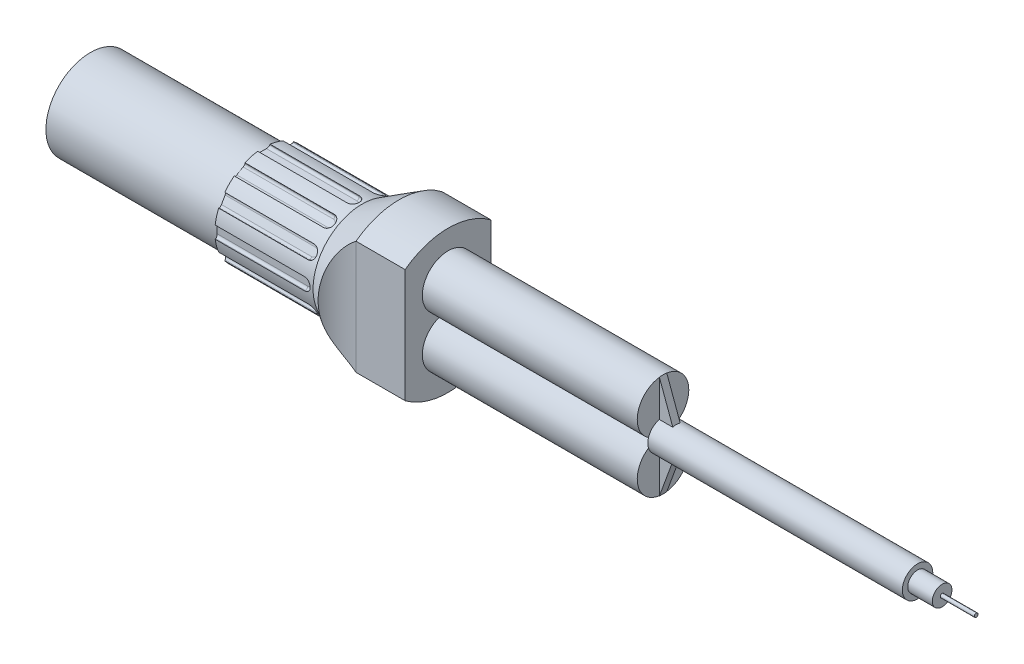
SolidWorks part; units mm, degrees
ref_plane "Ebene vorne" through (0, 0, 0) normal (0, 0, 1) x (1, 0, 0)
ref_plane "Ebene oben" through (0, 0, 0) normal (0, 1, 0) x (1, 0, 0)
ref_plane "Ebene rechts" through (0, 0, 0) normal (1, 0, 0) x (0, 0, -1)
sketch "Skizze1" plane through (0, 0, 0) normal (0, 1, 0) x (1, 0, 0)
  line L0 (0, 0) -> (0, 3.75)
  line L1 (0, 3.75) -> (3, 3.75)
  line L2 (3, 3.75) -> (8, 18.1)
  line L3 (8, 18.1) -> (78, 18.1)
  line L4 (78, 18.1) -> (78.662, 20)
  line L5 (78.662, 20) -> (118.662, 20)
  line L6 (118.662, 20) -> (133.662, 29)
  line L7 (133.662, 29) -> (153.662, 29)
  line L8 (153.662, 29) -> (153.662, 0)
  line L9 (153.662, 0) -> (0, 0) construction
  line L10 (0, 0) -> (153.662, 0)
  dimension "D1" = 7.5
  dimension "D2" = 3
  dimension "D3" = 36.2
  dimension "D4" = 5
  dimension "D5" = 70
  dimension "D6" = 58
  dimension "D7" = 20
  dimension "D8" = 15
  dimension "D9" = 40
  dimension "D10" = 40
revolve "Rotation1" add sketch "Skizze1" angle 360 about L9
sketch "Skizze2" plane through (0, 0, 0) normal (0, 1, 0) x (1, 0, 0)
  line L0 (153.662, 17.5) -> (133.662, 17.5)
  line L1 (153.662, -29) -> (153.662, 29) construction
  line L3 (133.662, 29) -> (118.662, 20) construction
  line L4 (133.662, 29) -> (153.662, 29)
  line L5 (153.662, 29) -> (133.662, 29) construction
  line L6 (153.662, 29) -> (153.662, 17.5)
  line L7 (0, 0) -> (153.662, 0) construction
  line L8 (123.8009, 23.0833) -> (133.662, 29)
  line L9 (133.662, 29) -> (118.662, 20) construction
  line L10 (123.8009, -23.0833) -> (133.662, -29)
  line L11 (153.662, -29) -> (153.662, -17.5)
  line L12 (133.662, -29) -> (153.662, -29)
  line L13 (153.662, -17.5) -> (133.662, -17.5)
  arc A0 (133.662, 17.5) -> (123.8009, 23.0833) centre (133.662, 29) cw
  arc A1 (133.662, -17.5) -> (123.8009, -23.0833) centre (133.662, -29) ccw
  dimension "D1" = 35
extrude "Schnitt-Linear austragen1" cut sketch "Skizze2" against normal through all and the other way through all
sketch "Skizze3" plane through (153.662, 0, 0) normal (1, 0, 0) x (0, 0, -1)
  line L0 (3.2016, 0.5) -> (3.2016, -0.5)
  line L1 (-3.2016, 0.5) -> (-3.2016, -0.5)
  arc A0 (3.2016, 0.5) -> (-3.2016, 0.5) centre (0, 10.5) ccw
  arc A1 (-3.2016, -0.5) -> (3.2016, -0.5) centre (0, -10.5) ccw
  dimension "D1" = 21
  dimension "D2" = 21
  dimension "D3" = 1
  dimension "D4" = 1
extrude "Aufsatz-Linear austragen3" add sketch "Skizze3" along normal blind 87.5 contours A0
sketch "Skizze5" plane through (241.162, 0, 0) normal (1, 0, 0) x (0, 0, -1)
  circle A0 centre (0, 0) radius 6.2
  dimension "D1" = 12.4
extrude "Aufsatz-Linear austragen6" add sketch "Skizze5" along normal blind 103.64
sketch "Skizze4" plane through (0, 0, 0) normal (0, 0, 1) x (1, 0, 0)
  line L0 (241.162, 21) -> (246.662, 6)
  line L2 (246.662, -6) -> (241.162, -21)
  line L3 (241.162, -21) -> (241.162, -6)
  line L4 (246.662, 6) -> (241.162, 6)
  line L5 (246.662, -6) -> (241.162, -6)
  line L6 (241.162, 6) -> (241.162, 21)
  dimension "D1" = 5.5
  dimension "D2" = 12
  dimension "D3" = 5.5
extrude "Aufsatz-Linear austragen4" add sketch "Skizze4" along normal blind 1.5 and the other way blind 1.5
sketch3d "3D-Skizze1"
  point P0 (94.6855, -7.5179, -18.5333)
ref_plane "Ebene1" through (0, 0, -18.5333) normal (0, 0, -1) x (1, 0, 0)
sketch "Skizze6" plane through (0, 0, -18.5333) normal (0, 0, -1) x (1, 0, 0)
  line L0 (78, 2.5) -> (115, 2.5)
  line L1 (78, -18.1) -> (78, 18.1) construction
  line L2 (115, -2.5) -> (78, -2.5)
  line L3 (78, 2.5) -> (78, -2.5)
  arc A0 (115, 2.5) -> (115, -2.5) centre (115, 0) cw
  dimension "D2" = 2.5
  dimension "D1" = 37
extrude "Schnitt-Linear austragen3" cut sketch "Skizze6" along normal blind 6.2
fillet "Verrundung2" radius 1 3 edges at (96.6047, 2.5, -18.5333) (117.5, 0, -18.5333) (96.6047, -2.5, -18.5333)
pattern_circular "Kreismuster1" count 12 every 30 about axis through (0, 0, 0) along (1, 0, 0) of "Schnitt-Linear austragen3", "Verrundung2"
sketch "Skizze7" plane through (344.802, 0, 0) normal (1, 0, 0) x (0, 0, -1)
  circle A0 centre (0, 0) radius 4
  dimension "D1" = 8
extrude "Aufsatz-Linear austragen7" add sketch "Skizze7" along normal blind 10
sketch "Skizze8" plane through (354.802, 0, 0) normal (1, 0, 0) x (0, 0, -1)
  circle A0 centre (0, 0) radius 0.75
  dimension "D1" = 1.5
extrude "Aufsatz-Linear austragen8" add sketch "Skizze8" along normal blind 13.86
